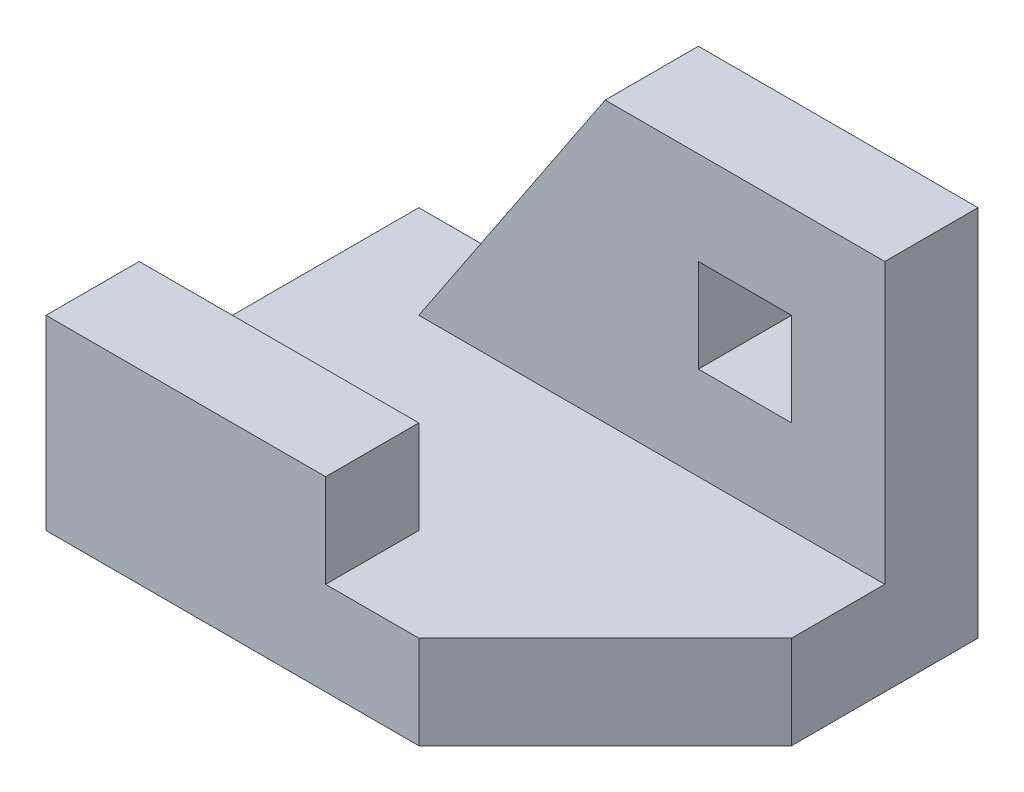
SolidWorks part; units mm, degrees
ref_plane "前基準面" through (0, 0, 0) normal (0, 0, 1) x (1, 0, 0)
ref_plane "上基準面" through (0, 0, 0) normal (0, 1, 0) x (1, 0, 0)
ref_plane "右基準面" through (0, 0, 0) normal (1, 0, 0) x (0, 0, -1)
sketch "草圖1" plane through (0, 0, 0) normal (0, 1, 0) x (1, 0, 0)
  line L0 (0, 0) -> (0, 4)
  line L1 (0, 4) -> (6, 4)
  line L2 (6, 4) -> (6, 2)
  line L3 (6, 2) -> (4, 0)
  line L4 (4, 0) -> (0, 0)
  dimension "D1" = 4
  dimension "D2" = 6
  dimension "D3" = 4
  dimension "D4" = 2
extrude "填料-伸長1" add sketch "草圖1" along normal blind 1
sketch "草圖2" plane through (0, 0, 0) normal (0, 0, 1) x (1, 0, 0)
  line L0 (0, 1) -> (0, 2)
  line L4 (0, 2) -> (3, 2)
  line L5 (3, 2) -> (3, 1)
  line L6 (0, 1) -> (4, 1) construction
  line L7 (3, 1) -> (0, 1)
  dimension "D1" = 1
  dimension "D2" = 3
extrude "填料-伸長2" add sketch "草圖2" against normal blind 1 contours L4 L5 L7 L0
sketch "草圖3" plane through (0, 0, -4) normal (0, 0, -1) x (-1, 0, 0)
  line L0 (-6, 1) -> (-6, 4)
  line L1 (-6, 4) -> (-3, 4)
  line L2 (-3, 4) -> (-1, 1)
  line L3 (-3, 1) -> (0, 1) construction
  line L4 (-1, 1) -> (-6, 1)
  dimension "D1" = 3
  dimension "D2" = 5
  dimension "D3" = 3
extrude "填料-伸長3" add sketch "草圖3" against normal blind 1
sketch "草圖4" plane through (0, 0, -4) normal (0, 0, -1) x (-1, 0, 0)
  line L3 (-5, 3) -> (-4, 3)
  line L4 (-4, 3) -> (-4, 2)
  line L5 (-4, 2) -> (-5, 2)
  line L6 (-5, 2) -> (-5, 3)
  dimension "D3" = 1
  dimension "D4" = 1
extrude "除料-伸長1" cut sketch "草圖4" against normal blind 1
